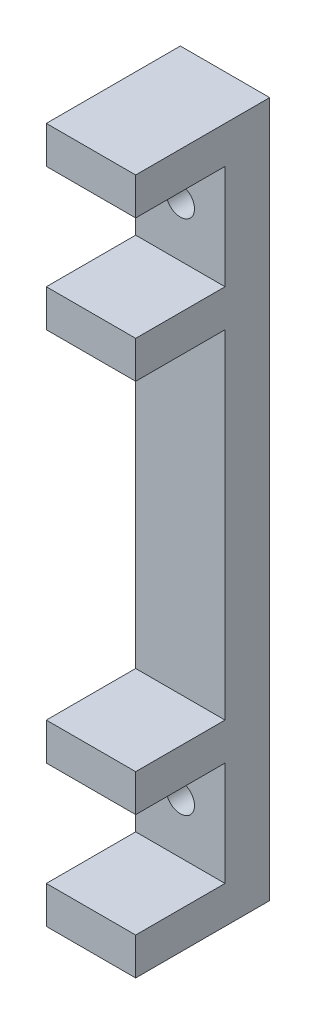
SolidWorks part; units mm, degrees
ref_plane "Plan de face" through (0, 0, 0) normal (0, 0, 1) x (1, 0, 0)
ref_plane "Plan de dessus" through (0, 0, 0) normal (0, 1, 0) x (1, 0, 0)
ref_plane "Plan de droite" through (0, 0, 0) normal (1, 0, 0) x (0, 0, -1)
sketch "Esquisse1" plane through (0, 0, 0) normal (0, 0, 1) x (1, 0, 0)
  line L1 (-3, -4) -> (3, -4)
  line L2 (-3, -4) -> (-3, 38.7)
  line L3 (-3, 38.7) -> (3, 38.7)
  line L4 (3, -4) -> (3, 38.7)
  circle A0 centre (0, 0) radius 0.95
  circle A1 centre (0, 34.7) radius 0.95
  dimension "D5" = 1.9
  dimension "D6" = 1.9
  dimension "D1" = 6
  dimension "D2" = 42.7
  dimension "D3" = 3
  dimension "D4" = 4
  dimension "D7" = 4
extrude "Boss.-Extru.1" add sketch "Esquisse1" along normal blind 3
sketch "Esquisse2" plane through (0, 0, 3) normal (0, 0, 1) x (1, 0, 0)
  line L0 (-0.95, 34.7) -> (0.95, 34.7) construction
  line L1 (3, 3.5) -> (3, 6)
  line L2 (-3, 38.2) -> (3, 38.2)
  line L3 (-3, 38.2) -> (-3, 40.7)
  line L4 (-3, 40.7) -> (3, 40.7)
  line L5 (-3, 38.7) -> (-3, -4) construction
  line L6 (-3, 31.2) -> (3, 31.2)
  line L7 (-3, 31.2) -> (-3, 28.7)
  line L8 (-3, 28.7) -> (3, 28.7)
  line L9 (3, 31.2) -> (3, 28.7)
  line L10 (3, -4) -> (3, 38.7) construction
  line L11 (-3, 17.35) -> (3, 17.35) construction
  line L12 (-3, 6) -> (3, 6)
  line L13 (-3, 3.5) -> (-3, 6)
  line L14 (-3, 3.5) -> (3, 3.5)
  line L15 (3, -3.5) -> (3, -6)
  line L16 (-3, -6) -> (3, -6)
  line L17 (-3, -3.5) -> (-3, -6)
  line L18 (-3, -3.5) -> (3, -3.5)
  line L20 (3, 38.2) -> (3, 40.7)
  circle A0 centre (0, 34.7) radius 0.95 construction
  dimension "D1" = 3.5
  dimension "D2" = 2.5
  dimension "D3" = 3.5
  dimension "D4" = 2.5
extrude "Boss.-Extru.2" add sketch "Esquisse2" along normal blind 6 and the other way up to surface other way up to face at (0.95, 0, 0)
